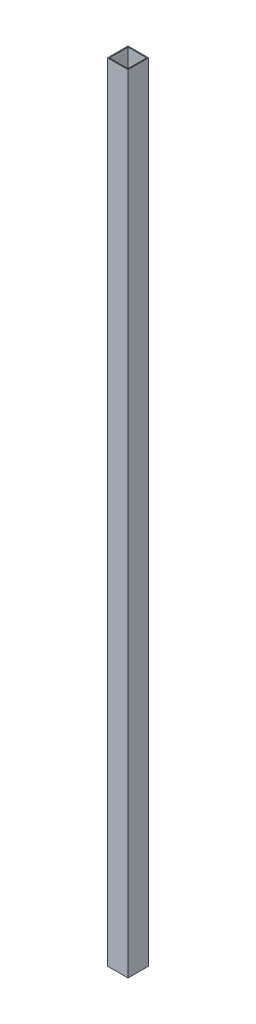
SolidWorks part; units mm, degrees
ref_plane "Front Plane" through (0, 0, 0) normal (0, 0, 1) x (1, 0, 0)
ref_plane "Top Plane" through (0, 0, 0) normal (0, 1, 0) x (1, 0, 0)
ref_plane "Right Plane" through (0, 0, 0) normal (1, 0, 0) x (0, 0, -1)
sketch "Sketch1" plane through (0, 0, 0) normal (0, 1, 0) x (1, 0, 0)
  line L0 (0, 0) -> (0, 50)
  line L1 (0, 50) -> (50, 50)
  line L2 (50, 50) -> (50, 0)
  line L3 (50, 0) -> (0, 0)
  line L4 (2.2, 47.8) -> (47.8, 47.8)
  line L5 (47.8, 47.8) -> (47.8, 2.2)
  line L6 (47.8, 2.2) -> (2.2, 2.2)
  line L7 (2.2, 2.2) -> (2.2, 47.8)
  dimension "D1" = 50
  dimension "D2" = 50
  dimension "D3" = 2.2
extrude "Boss-Extrude1" add sketch "Sketch1" along normal blind 1923
equation "\"SquareTube_length\"=1923.0"
equation "\"D1@Boss-Extrude1\"=\"SquareTube_length\""
equation "\"CarBeamWidth\"=700.0"
equation "\"MetalSheet_3mm_length\"=5030.0"
equation "\"MetalSheet_3mm_width\"=1923.0"
equation "\"MetalSheet_3mm_FloorCut_L_length\"=1764.0"
equation "\"MetalSheet_3mm_FloorCut_L_disdance\"=1665.0"
equation "\"MetalSheet_3mm_FloorCut_R_length\"=1764.0"
equation "\"MetalSheet_3mm_FloorCut_R_disdance\"=1665.0"
equation "\"indoorHeight\"=1940.0"
equation "\"x\"=66.0"
equation "\"da\"=62.0"
equation "\"SquareTube_wheel_length\"= 750"
equation "\"channelSteel_length\"=5030.0"
equation "\"SquareTube_inFront1_cutDepth50_R\"=0.5"
equation "\"SquareTube_inFront1_cutDepth50_L\"=0.5"
equation "\"SquareTube_inFront2_cutDepth50_R\"=0.5"
equation "\"SquareTube_inFront2_cutDepth50_L\"=0.5"
equation "\"SquareTube_inFront3_cutDepth50_R\"=0.5"
equation "\"SquareTube_inFront3_cutDepth50_L\"=0.5"
equation "\"SquareTube_inFront4_cutDepth50_R\"=0.5"
equation "\"SquareTube_inFront4_cutDepth50_L\"=0.5"
equation "\"SquareTube_inFront5_cutDepth50_R\"=50"
equation "\"SquareTube_inFront5_cutDepth50_L\"=50"
equation "\"SquareTube_inFront6_cutDepth50_R\"=50"
equation "\"SquareTube_inFront6_cutDepth50_L\"=50"
equation "\"SquareTube_inFront7_cutDepth50_R\"=50"
equation "\"SquareTube_inFront7_cutDepth50_L\"=50"
equation "\"SquareTube_inFront8_cutDepth50_R\"=50"
equation "\"SquareTube_inFront8_cutDepth50_L\"=50"
equation "\"SquareTube_inFront9_cutDepth50_R\"=50"
equation "\"SquareTube_inFront9_cutDepth50_L\"=50"
equation "\"SquareTube_inFront10_cutDepth50_R\"=50"
equation "\"SquareTube_inFront10_cutDepth50_L\"=50"
equation "\"SquareTube_inBack1_cutDepth50_R\"=50"
equation "\"SquareTube_inBack1_cutDepth50_L\"=50"
equation "\"SquareTube_inBack2_cutDepth50_R\"=50"
equation "\"SquareTube_inBack2_cutDepth50_L\"=50"
equation "\"SquareTube_inBack3_cutDepth50_R\"=50"
equation "\"SquareTube_inBack3_cutDepth50_L\"=50"
equation "\"SquareTube_inBack4_cutDepth50_R\"=50"
equation "\"SquareTube_inBack4_cutDepth50_L\"=50"
equation "\"SquareTube_inBack5_cutDepth50_R\"=50"
equation "\"SquareTube_inBack5_cutDepth50_L\"=50"
equation "\"SquareTube_inBack6_cutDepth50_R\"=0.5"
equation "\"SquareTube_inBack6_cutDepth50_L\"=0.5"
